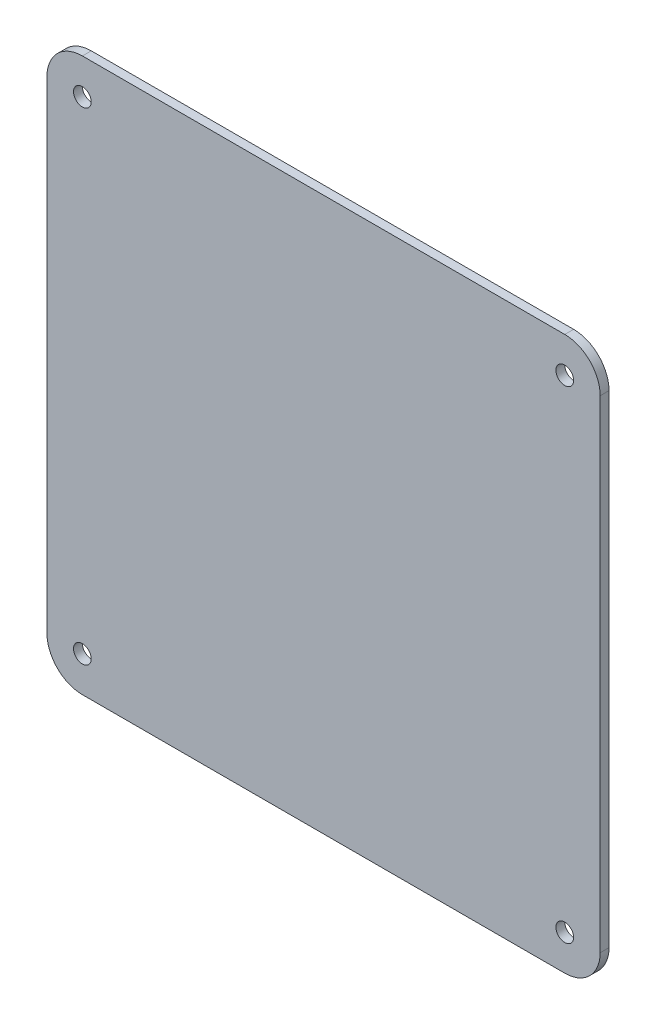
SolidWorks part; units mm, degrees
material "ABS PC"
ref_plane "Front Plane" through (0, 0, 0) normal (0, 0, 1) x (1, 0, 0)
ref_plane "Top Plane" through (0, 0, 0) normal (0, 1, 0) x (1, 0, 0)
ref_plane "Right Plane" through (0, 0, 0) normal (1, 0, 0) x (0, 0, -1)
sketch "Sketch1" plane through (0, 0, 0) normal (0, 0, 1) x (1, 0, 0)
  line L1 (-109, 125) -> (109, 125)
  line L2 (-125, 109) -> (-125, -109)
  line L3 (-109, -125) -> (109, -125)
  line L4 (125, 109) -> (125, -109)
  line L5 (-125, 125) -> (125, -125) construction
  line L6 (-125, -125) -> (125, 125) construction
  arc A0 (-125, -109) -> (-109, -125) centre (-109, -109) ccw
  arc A1 (109, -125) -> (125, -109) centre (109, -109) ccw
  arc A2 (109, 125) -> (125, 109) centre (109, 109) cw
  arc A3 (-109, 125) -> (-125, 109) centre (-109, 109) ccw
  circle A4 centre (-109, -109) radius 4
  circle A5 centre (-109, 109) radius 4
  circle A6 centre (109, 109) radius 4
  circle A7 centre (109, -109) radius 4
  point P0 (0, 0)
  dimension "D3" = 16
  dimension "D4" = 8
  dimension "D5" = 8
  dimension "D6" = 8
  dimension "D7" = 8
  dimension "D1" = 250
  dimension "D2" = 250
extrude "Boss-Extrude1" add sketch "Sketch1" along normal blind 4
